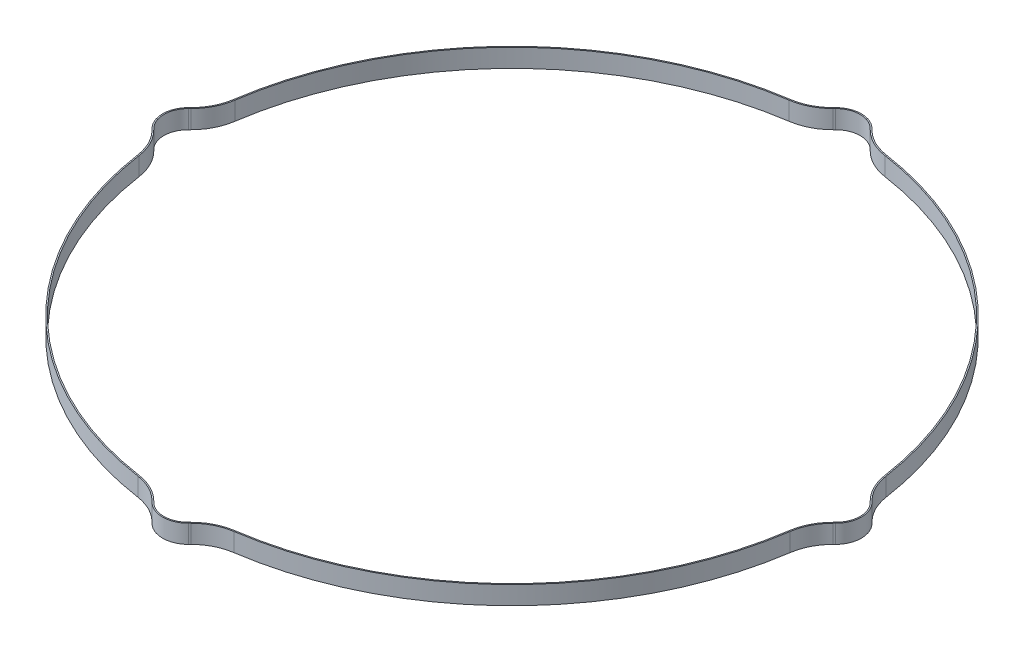
SolidWorks part; units mm, degrees
ref_plane "Front" through (0, 0, 0) normal (0, 0, 1) x (1, 0, 0)
ref_plane "Top" through (0, 0, 0) normal (0, 1, 0) x (1, 0, 0)
ref_plane "Right" through (0, 0, 0) normal (1, 0, 0) x (0, 0, -1)
sketch "Sketch1" plane through (0, 0, 0) normal (0, 1, 0) x (1, 0, 0)
  line L0 (0, 0) -> (526.4354, 0) construction
  line L5 (35.921, -708.571) -> (38.6565, -705.8356)
  line L6 (708.571, 35.921) -> (705.8356, 38.6565)
  line L7 (-35.921, 708.571) -> (-38.6565, 705.8356)
  line L8 (-708.571, -35.921) -> (-705.8356, -38.6565)
  line L9 (-38.6565, -705.8356) -> (-35.921, -708.571)
  line L10 (-705.8356, 38.6565) -> (-708.571, 35.921)
  line L11 (705.8356, -38.6565) -> (708.571, -35.921)
  line L12 (38.6565, 705.8356) -> (35.921, 708.571)
  line L13 (711.2, 0) -> (744.4921, 0) construction
  arc A0 (-99.2874, 675.3658) -> (-675.3658, 99.2874) centre (0, 0) ccw
  circle A1 centre (0, 0) radius 526.4354 construction
  arc A2 (-675.3658, -99.2874) -> (-99.2874, -675.3658) centre (0, 0) ccw
  arc A3 (99.2874, -675.3658) -> (675.3658, -99.2874) centre (0, 0) ccw
  arc A4 (675.3658, 99.2874) -> (99.2874, 675.3658) centre (0, 0) ccw
  arc A5 (35.921, 708.571) -> (-35.921, 708.571) centre (0, 672.65) ccw
  arc A6 (708.571, 35.921) -> (708.571, -35.921) centre (672.65, 0) cw
  arc A7 (-35.921, -708.571) -> (35.921, -708.571) centre (0, -672.65) ccw
  arc A8 (-708.571, 35.921) -> (-708.571, -35.921) centre (-672.65, 0) ccw
  arc A9 (-99.2874, -675.3658) -> (-38.6565, -705.8356) centre (-114.9886, -782.1678) cw
  arc A10 (99.2874, -675.3658) -> (38.6565, -705.8356) centre (114.9886, -782.1678) ccw
  arc A11 (675.3658, -99.2874) -> (705.8356, -38.6565) centre (782.1678, -114.9886) cw
  arc A12 (675.3658, 99.2874) -> (705.8356, 38.6565) centre (782.1678, 114.9886) ccw
  arc A13 (-99.2874, 675.3658) -> (-38.6565, 705.8356) centre (-114.9886, 782.1678) ccw
  arc A14 (-675.3658, 99.2874) -> (-705.8356, 38.6565) centre (-782.1678, 114.9886) cw
  arc A15 (-705.8356, -38.6565) -> (-675.3658, -99.2874) centre (-782.1678, -114.9886) cw
  arc A16 (99.2874, 675.3658) -> (38.6565, 705.8356) centre (114.9886, 782.1678) cw
  point P15 (-673.0988, -74.685)
  point P19 (711.2, 34.1105)
  point P31 (-64.9655, -679.5266)
  point P34 (64.9655, -679.5266)
  point P37 (679.5266, -64.9655)
  point P40 (679.5266, 64.9655)
  point P43 (-35.921, -695.3476)
  point P48 (-679.5266, -64.9655)
  dimension "D1" = 1365.25
  dimension "D2" = 50.8
  dimension "D3" = 107.95
  dimension "D4" = 107.95
extrude "Extrude-Thin1" add sketch "Sketch1" along normal blind 38.1 thin
